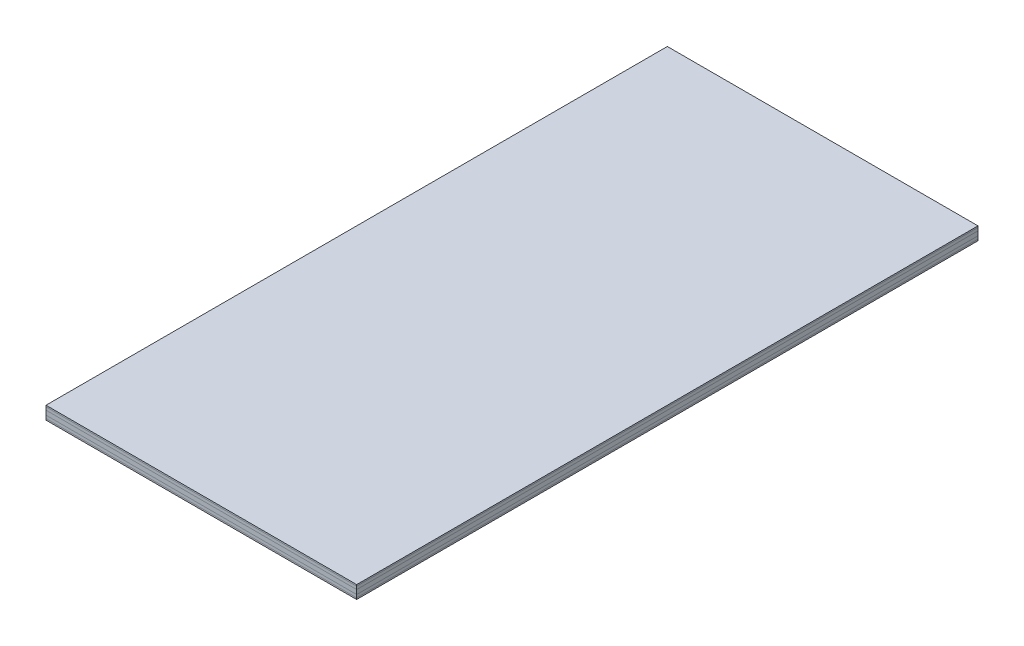
SolidWorks part; units mm, degrees
ref_plane "Front Plane" through (0, 0, 0) normal (0, 0, 1) x (1, 0, 0)
ref_plane "Top Plane" through (0, 0, 0) normal (0, 1, 0) x (1, 0, 0)
ref_plane "Right Plane" through (0, 0, 0) normal (1, 0, 0) x (0, 0, -1)
sketch "Sketch1" plane through (0, 0, 0) normal (0, 1, 0) x (1, 0, 0)
  line L0 (-304.8, 609.6) -> (304.8, 609.6) construction
  line L1 (304.8, 609.6) -> (304.8, -609.6) construction
  line L2 (0, 609.6) -> (0, 0) construction
  line L3 (0, 0) -> (304.8, 0) construction
  dimension "Width" = 609.6
  dimension "Length" = 1219.2
sketch "Sketch2" plane through (0, 0, 0) normal (1, 0, 0) x (0, 0, -1)
  line L0 (609.6, 0) -> (609.6, -25.4) construction
  dimension "Thickness" = 25.4
sketch "Sketch3" plane through (0, 0, 0) normal (0, 1, 0) x (1, 0, 0)
  line L1 (-304.8, 609.6) -> (304.8, 609.6)
  line L2 (-304.8, 609.6) -> (-304.8, -609.6)
  line L3 (-304.8, -609.6) -> (304.8, -609.6)
  line L4 (304.8, 609.6) -> (304.8, -609.6)
extrude "Boss-Extrude1" add sketch "Sketch3" against normal up to vertex (25.4 mm away) up to point (0, -25.4, -609.6)
sketch "Sketch4" plane through (0, 0, 0) normal (0, 0, 1) x (1, 0, 0)
  line L0 (0, -11.2889) -> (0, -14.1111) construction
  line L1 (-335.28, -22.5778) -> (335.28, -22.5778)
  line L2 (0, 0) -> (0, -25.4) construction
  line L3 (0, -11.2889) -> (0, -8.4667) construction
  line L4 (0, -14.1111) -> (0, -16.9333) construction
  line L5 (0, -8.4667) -> (0, -5.6444) construction
  line L6 (0, -5.6444) -> (0, -2.8222) construction
  line L7 (0, -2.8222) -> (0, 0) construction
  line L8 (0, -16.9333) -> (0, -19.7556) construction
  line L9 (0, -19.7556) -> (0, -22.5778) construction
  line L10 (0, -22.5778) -> (0, -25.4) construction
  line L11 (-335.28, -16.9333) -> (335.28, -16.9333)
  line L12 (-335.28, -2.8222) -> (335.28, -2.8222)
  line L13 (-335.28, -8.4667) -> (335.28, -8.4667)
  point P5 (0, -12.7)
  point P16 (0, -22.5778)
  point P19 (0, -16.9333)
  point P23 (0, -2.8222)
  point P25 (0, -8.4667)
  dimension "D1" = 670.56
split "Split1" trim tools "Sketch4" bodies to split 104 resulting bodies 105 106 107 108 109
sketch "Sketch6" plane through (0, 0, 0) normal (0, 1, 0) x (1, 0, 0)
  line L1 (-304.8, -609.6) -> (304.8, -609.6) construction
  line L2 (215.9, -609.6) -> (215.9, 0)
  line L3 (215.9, 0) -> (304.8, 0)
  line L4 (304.8, -609.6) -> (304.8, 609.6) construction
  line L6 (-304.8, 609.6) -> (-304.8, -609.6)
  line L7 (-304.8, -609.6) -> (304.8, -609.6)
  line L8 (304.8, -609.6) -> (304.8, 609.6)
  line L9 (304.8, 609.6) -> (-304.8, 609.6)
equation "\"D1@Sketch4\"=\"Width@Sketch1\"*1.1"
